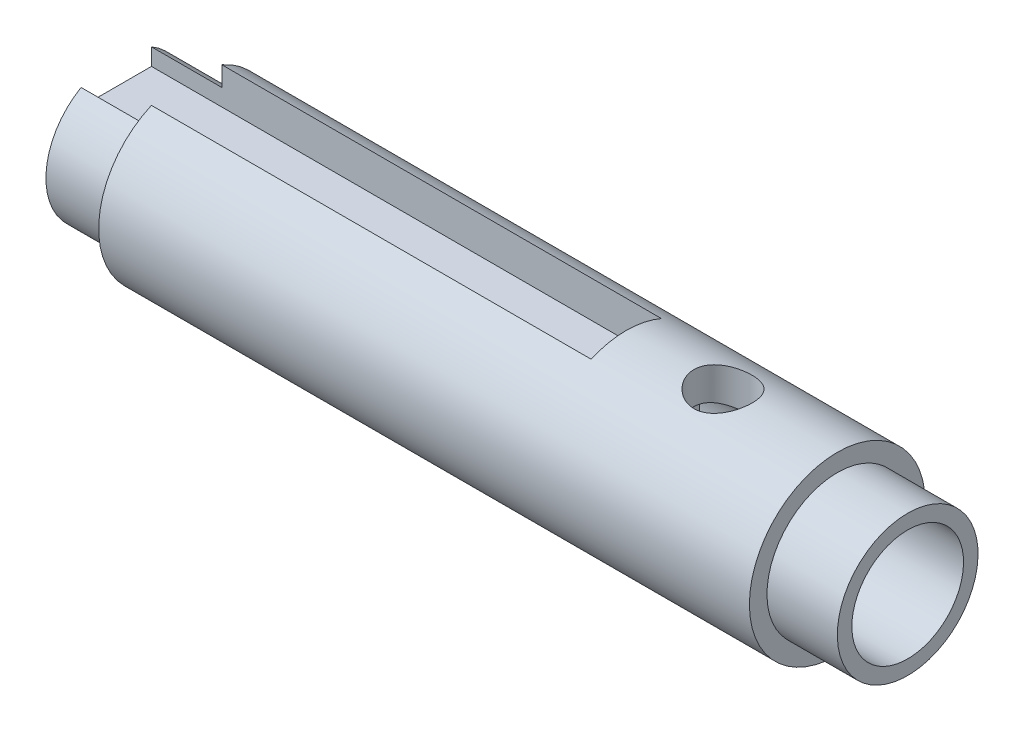
SolidWorks part; units mm, degrees
material "Alloy Steel"
ref_plane "Front Plane" through (0, 0, 0) normal (0, 0, 1) x (1, 0, 0)
ref_plane "Top Plane" through (0, 0, 0) normal (0, 1, 0) x (1, 0, 0)
ref_plane "Right Plane" through (0, 0, 0) normal (1, 0, 0) x (0, 0, -1)
sketch "Sketch1" plane through (0, 0, 0) normal (0, 0, 1) x (1, 0, 0)
  line L0 (22.5, 0) -> (-22.5, 0) construction
  line L1 (-22.5, 0) -> (-22.5, 4)
  line L2 (-22.5, 4) -> (-18.5, 4)
  line L3 (22.5, 0) -> (22.5, 4)
  line L4 (22.5, 4) -> (18.5, 4)
  line L5 (-18.5, 4) -> (-18.5, 5)
  line L6 (18.5, 4) -> (18.5, 5)
  line L7 (-18.5, 5) -> (18.5, 5)
  line L8 (-22.5, 0) -> (22.5, 0)
  point P4 (0, 0)
  dimension "D1" = 45
  dimension "D2" = 4
  dimension "D3" = 4
  dimension "D4" = 1
revolve "Revolve1" add sketch "Sketch1" angle 360 about L0
ref_plane "Plane1" through (22.5, 0, 0) normal (1, 0, 0) x (0, 0, -1)
sketch "Sketch3" plane through (22.5, 0, 0) normal (1, 0, 0) x (0, 0, -1)
  circle A0 centre (0, 0) radius 4 construction
  circle A1 centre (0, 0) radius 4
  circle A2 centre (0, 0) radius 3.175
  dimension "D1" = 6.35
extrude "Cut-Extrude2" cut sketch "Sketch3" against normal blind 15 contours A2
ref_plane "Plane2" through (0, 5, 0) normal (0, 1, 0) x (1, 0, 0)
hole_wizard "M4x0.7 Tapped Hole1" positions "Sketch4" profile "Sketch5" tap size "M4x0.7" standard "ANSI Metric"
sketch "Sketch4" plane through (0, 5, 0) normal (0, 1, 0) x (1, 0, 0)
  line L1 (18.5, -5) -> (18.5, 5) construction
  point P0 (12, 0)
  dimension "D1" = 6.5
sketch "Sketch5" plane through (12, 5, 0) normal (1, 0, 0) x (0, 0, 1)
  line L0 (0, 0) -> (0, 7.9914)
  line L1 (0, 7.9914) -> (1.65, 7)
  line L2 (1.65, 7) -> (1.65, 0)
  line L5 (1.65, 0) -> (0, 0)
  line L10 (0, 7.9914) -> (-1.65, 7) construction
  line L11 (0, -6.35) -> (0, 107.95) construction
  dimension "Tap Drill Dia." = 3.3
  dimension "Tap Drill Depth" = 7
  dimension "Drill Angle" = 118
sketch "Sketch6" plane through (18.5, 0, 0) normal (1, 0, 0) x (0, 0, -1)
  line L0 (-2.5515, -4.3) -> (2.5515, -4.3)
  line L1 (-4.3, -2.5515) -> (-4.3, 2.5515)
  line L2 (-4.3, 0) -> (-5, 0) construction
  line L3 (0, -4.3) -> (0, -5) construction
  circle A0 centre (0, 0) radius 5 construction
  circle A1 centre (0, 0) radius 5
  dimension "D1" = 0.7
sketch "Sketch7" plane through (-18.5, 0, 0) normal (-1, 0, 0) x (0, 0, 1)
  line L0 (8.2647, 5) -> (-8.2647, 5) construction
  line L1 (0, 5) -> (0, 0) construction
  line L2 (2, 2.5) -> (-2, 2.5)
  line L3 (2, 5) -> (-2, 5)
  line L4 (-2, 5) -> (-2, 2.5)
  line L5 (2, 5) -> (2, 2.5)
  circle A0 centre (0, 0) radius 5 construction
  circle A1 centre (0, 0) radius 5
  point P6 (0, 5)
  point P10 (0, 2.5)
  point P13 (0, 5)
  circle M5 centre (0, 0) radius 4
  circle M6 centre (0, 0) radius 5
  dimension "D1" = 2.5
  dimension "D2" = 4
extrude "Key Cut" cut sketch "Sketch7" against normal blind 25 and the other way blind 25 contours L5 L4 M6 M5 | L5 L4 L2 M5
equation "\"t1\"=2.5"
equation "\"D1@Sketch7\"=\"t1\""
